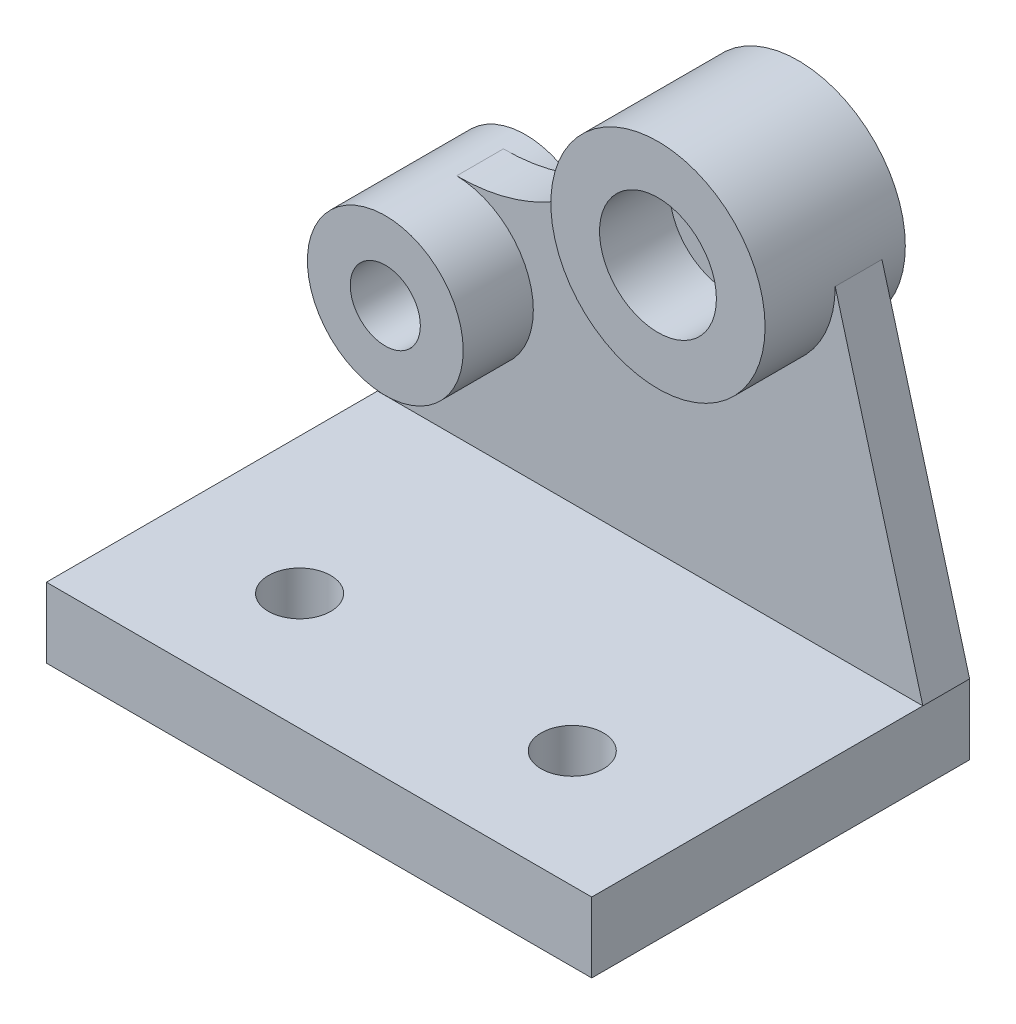
SolidWorks part; units mm, degrees
ref_plane "Front Plane" through (0, 0, 0) normal (0, 0, 1) x (1, 0, 0)
ref_plane "Top Plane" through (0, 0, 0) normal (0, 1, 0) x (1, 0, 0)
ref_plane "Right Plane" through (0, 0, 0) normal (1, 0, 0) x (0, 0, -1)
sketch "Sketch1" plane through (0, 0, 0) normal (0, 0, 1) x (1, 0, 0)
  line L0 (0, 0) -> (140, 0)
  line L1 (140, 0) -> (140, 18)
  line L2 (140, 18) -> (0, 18)
  line L3 (0, 18) -> (0, 0)
  dimension "D1" = 140
  dimension "D2" = 18
extrude "Boss-Extrude1" add sketch "Sketch1" along normal blind 85
sketch "Sketch3" plane through (0, 18, 0) normal (0, 1, 0) x (1, 0, 0)
  line L0 (140, -85) -> (0, -85) construction
  line L2 (0, -85) -> (0, 0) construction
  line L3 (20, 10.0319) -> (20, -91.049) construction
  line L4 (90, 13.5018) -> (90, -95.2732) construction
  line L5 (140, -85) -> (140, 0) construction
  circle A0 centre (35, -55) radius 8
  circle A1 centre (105, -55) radius 8
  dimension "D3" = 16
  dimension "D6" = 16
  dimension "D1" = 30
  dimension "D2" = 70
  dimension "D4" = 35
  dimension "D5" = 30
  dimension "D7" = 20
  dimension "D8" = 50
extrude "Cut-Extrude2" cut sketch "Sketch3" against normal blind 18 contours A0 | A1
sketch "Sketch5" plane through (0, 0, 0) normal (0, 0, -1) x (-1, 0, 0)
  line L0 (-140, 0) -> (-140, 100)
  line L1 (-140, 100) -> (0, 100)
  line L2 (0, 100) -> (0, 0)
  line L3 (0, 0) -> (-140, 0)
  dimension "D1" = 100
  dimension "D2" = 140
extrude "Boss-Extrude5" add sketch "Sketch5" along normal blind 12
sketch "Sketch8" plane through (0, 0, 0) normal (0, 0, 1) x (1, 0, 0)
  line L0 (0, 100) -> (140, 100) construction
  line L1 (140, 18) -> (0, 18) construction
  line L2 (0, 18) -> (0, 100) construction
  line L5 (140, 100) -> (140, 18) construction
  circle A0 centre (20, 56) radius 9
  circle A1 centre (20, 56) radius 20
  circle A2 centre (90, 100) radius 27.5
  circle A3 centre (90, 100) radius 15
  dimension "D2" = 40
  dimension "D3" = 18
  dimension "D5" = 55
  dimension "D6" = 30
  dimension "D1" = 38
  dimension "D4" = 20
  dimension "D7" = 50
extrude "Boss-Extrude6" add sketch "Sketch8" along normal mid plane 36
sketch "Sketch10" plane through (0, 0, 0) normal (0, 0, 1) x (1, 0, 0)
  line L0 (117.5, 100) -> (140, 18)
  line L1 (140, 18) -> (140, 100)
  line L2 (140, 100) -> (117.5, 100)
  line L3 (62.5, 100) -> (0, 100)
  line L4 (0, 100) -> (0, 56)
  arc A0 (20, 76) -> (62.5, 100) centre (20.5418, 124.6708) ccw
  circle A1 centre (20, 56) radius 20 construction
  circle A2 centre (20, 56) radius 20 construction
  line M8 (140, 100) -> (117.5, 100)
  line M10 (62.5, 100) -> (0, 100)
  line M11 (0, 100) -> (0, 56)
  circle M12 centre (20, 56) radius 20
  line M15 (140, 18) -> (140, 100)
extrude "Cut-Extrude3" cut sketch "Sketch10" against normal blind 12 contours L0 M8 M15 | A0 M12 M10 M11
